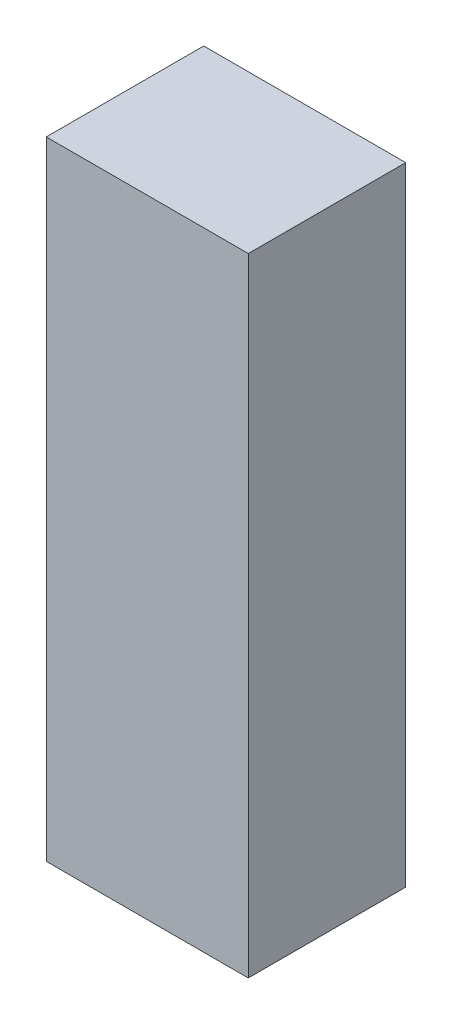
SolidWorks part; units mm, degrees
ref_plane "Plano frontal" through (0, 0, 0) normal (0, 0, 1) x (1, 0, 0)
ref_plane "Plano superior" through (0, 0, 0) normal (0, 1, 0) x (1, 0, 0)
ref_plane "Plano direito" through (0, 0, 0) normal (1, 0, 0) x (0, 0, -1)
sketch "Esboço1" plane through (0, 0, 0) normal (0, 0, 1) x (1, 0, 0)
  line L1 (17, 52.8) -> (-17, 52.8)
  line L2 (17, 52.8) -> (17, -52.8)
  line L3 (17, -52.8) -> (-17, -52.8)
  line L4 (-17, 52.8) -> (-17, -52.8)
  line L5 (17, 52.8) -> (-17, -52.8) construction
  line L6 (17, -52.8) -> (-17, 52.8) construction
  point P0 (0, 0)
  dimension "D1" = 105.6
  dimension "D2" = 34
extrude "Ressalto-extrusão1" add sketch "Esboço1" along normal blind 26.5
